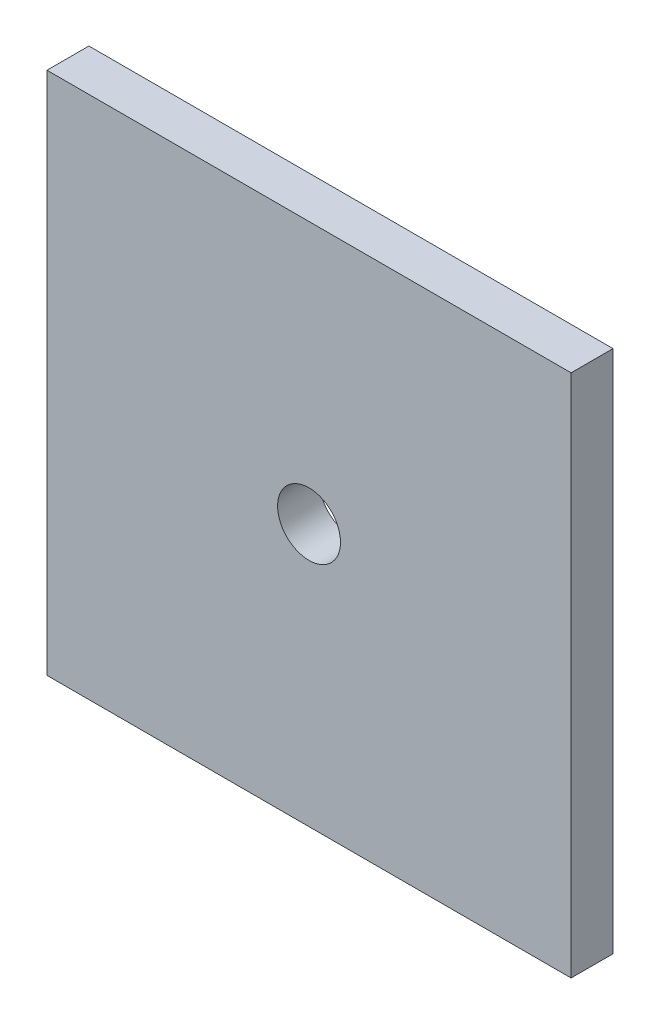
SolidWorks part; units mm, degrees
ref_plane "Front Plane" through (0, 0, 0) normal (0, 0, 1) x (1, 0, 0)
ref_plane "Top Plane" through (0, 0, 0) normal (0, 1, 0) x (1, 0, 0)
ref_plane "Right Plane" through (0, 0, 0) normal (1, 0, 0) x (0, 0, -1)
sketch "Sketch1" plane through (0, 0, 0) normal (0, 0, 1) x (1, 0, 0)
  line L1 (-18.75, -18.75) -> (18.75, -18.75)
  line L2 (-18.75, -18.75) -> (-18.75, 18.75)
  line L3 (-18.75, 18.75) -> (18.75, 18.75)
  line L4 (18.75, -18.75) -> (18.75, 18.75)
  line L5 (-18.75, -18.75) -> (18.75, 18.75) construction
  line L6 (-18.75, 18.75) -> (18.75, -18.75) construction
  circle A0 centre (0, 0) radius 2.25
  point P0 (0, 0)
  dimension "D3" = 4.5
  dimension "D1" = 37.5
  dimension "D2" = 37.5
extrude "Boss-Extrude1" add sketch "Sketch1" along normal blind 3
